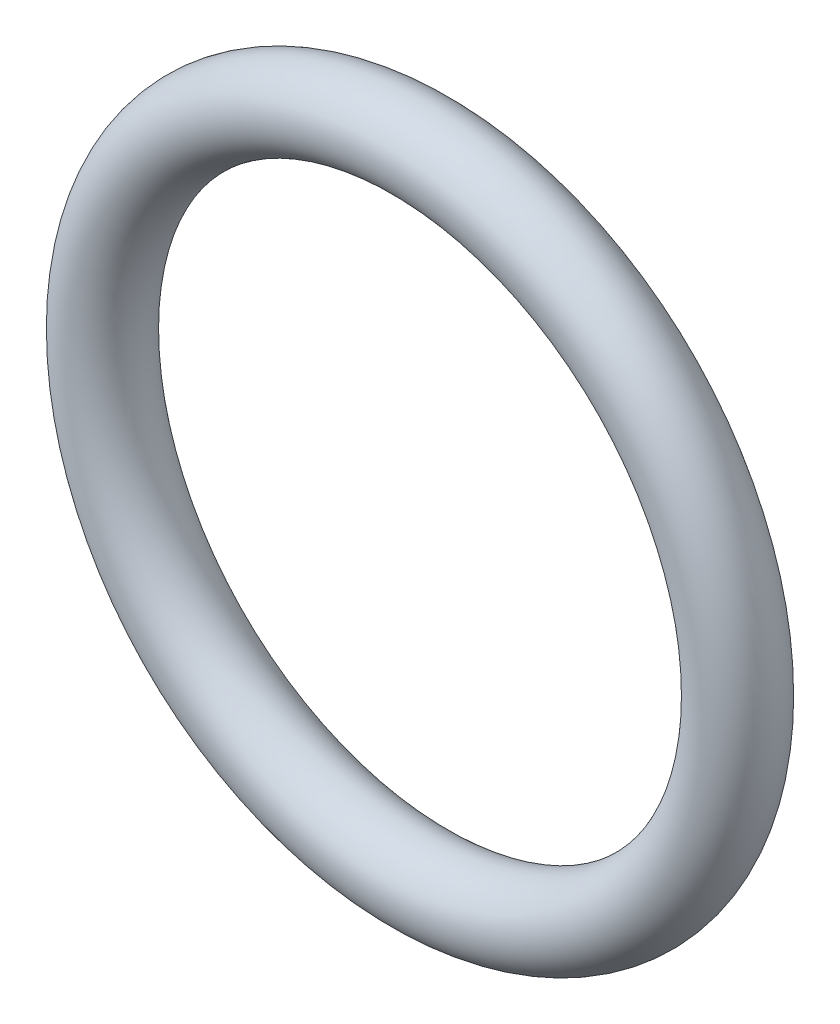
SolidWorks part; units mm, degrees
ref_plane "Front Plane" through (0, 0, 0) normal (0, 0, 1) x (1, 0, 0)
ref_plane "Top Plane" through (0, 0, 0) normal (0, 1, 0) x (1, 0, 0)
ref_plane "Right Plane" through (0, 0, 0) normal (1, 0, 0) x (0, 0, -1)
sketch "Sketch3" plane through (0, 0, 0) normal (0, 0, 1) x (1, 0, 0)
  circle A0 centre (0, 0) radius 16
  dimension "D1" = 32
sketch "Sketch4" plane through (0, 0, 0) normal (0, 1, 0) x (1, 0, 0)
  line L0 (-16, 0) -> (16, 0) construction
  circle A0 centre (-16, 0) radius 2
  point P4 (-16.0402, 0)
  point P5 (0, 0)
  dimension "D1" = 4
sweep "Sweep1" add profiles "Sketch4" path "Sketch3"
